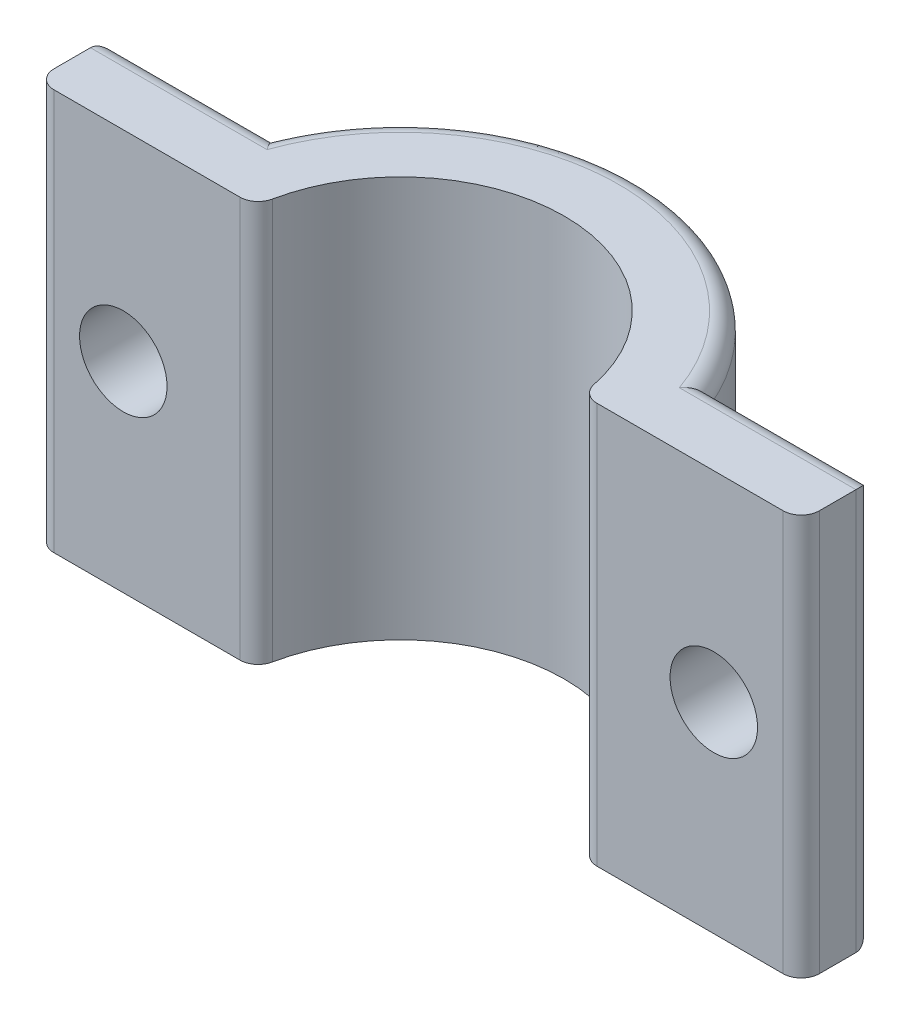
SolidWorks part; units mm, degrees
ref_plane "Front Plane" through (0, 0, 0) normal (0, 0, 1) x (1, 0, 0)
ref_plane "Top Plane" through (0, 0, 0) normal (0, 1, 0) x (1, 0, 0)
ref_plane "Right Plane" through (0, 0, 0) normal (1, 0, 0) x (0, 0, -1)
sketch "Sketch1" plane through (0, 0, 0) normal (0, 1, 0) x (1, 0, 0)
  line L0 (-10.5, 2.5) -> (-6, 2.5)
  line L1 (-6.4807, 0.5) -> (-10.5, 0.5)
  line L2 (-10.5, 2.5) -> (-10.5, 0.5)
  line L3 (6.4807, 0.5) -> (10.5, 0.5)
  line L4 (10.5, 0.5) -> (10.5, 2.5)
  line L5 (-6.4807, 0.5) -> (-4.4721, 0.5)
  line L6 (4.4721, 0.5) -> (6.4807, 0.5)
  line L7 (-6, 2.5) -> (-3.7417, 2.5) construction
  line L8 (-3.7417, 2.5) -> (3.7417, 2.5) construction
  line L9 (3.7417, 2.5) -> (6, 2.5) construction
  line L10 (6, 2.5) -> (10.5, 2.5)
  arc A0 (4.4721, 0.5) -> (-4.4721, 0.5) centre (0, 0) ccw
  arc A1 (6, 2.5) -> (-6, 2.5) centre (0, 0) ccw
  arc A2 (-4.4721, 0.5) -> (4.4721, 0.5) centre (0, 0) ccw construction
  circle A3 centre (0, 0) radius 4.5 construction
  arc A4 (-6.4807, 0.5) -> (6.4807, 0.5) centre (0, 0) ccw construction
  circle A5 centre (0, 0) radius 6.5 construction
  arc A6 (-6, 2.5) -> (-6.4807, 0.5) centre (0, 0) ccw construction
  arc A7 (6.4807, 0.5) -> (6, 2.5) centre (0, 0) ccw construction
  dimension "D1" = 9
  dimension "D6" = 2.5
  dimension "D4" = 2
  dimension "D5" = 21
  dimension "D3" = 2
extrude "Boss-Extrude1" add sketch "Sketch1" along normal blind 11 contours L10 A1 L0 L2 L1 L5 A0 L6 L3 L4
sketch "Sketch2" plane through (0, 0, -2.5) normal (0, 0, -1) x (-1, 0, 0)
  line L0 (-10.5, 5.5) -> (10.5, 5.5) construction
  line L1 (-10.5, 11) -> (-10.5, 0) construction
  line L2 (10.5, 11) -> (10.5, 0) construction
  circle A0 centre (-8.1, 5.5) radius 1.2
  circle A1 centre (8.1, 5.5) radius 1.2
  dimension "D1" = 2.4
  dimension "D2" = 2.4
  dimension "D3" = 2.4
  dimension "D4" = 2.4
extrude "Cut-Extrude1" cut sketch "Sketch2" against normal up to surface (2 mm away) up to face at (-7.4861, 5.5, -0.5)
fillet "Fillet1" radius 0.5 12 edges at (-10.5, 5.5, -0.5) (-4.4721, 5.5, -0.5) (4.4721, 5.5, -0.5) (10.5, 5.5, -0.5) (-10.5, 5.5, -2.5) (10.5, 5.5, -2.5) (8.25, 11, -2.5) (-8.25, 11, -2.5) (-8.25, 0, -2.5) (8.25, 0, -2.5) (0, 11, -6.5) (0, 0, -6.5)
equation "\"D4@Sketch2\"=\"D3@Sketch2\""
equation "\"D2@Sketch2\"=\"D1@Sketch2\""
